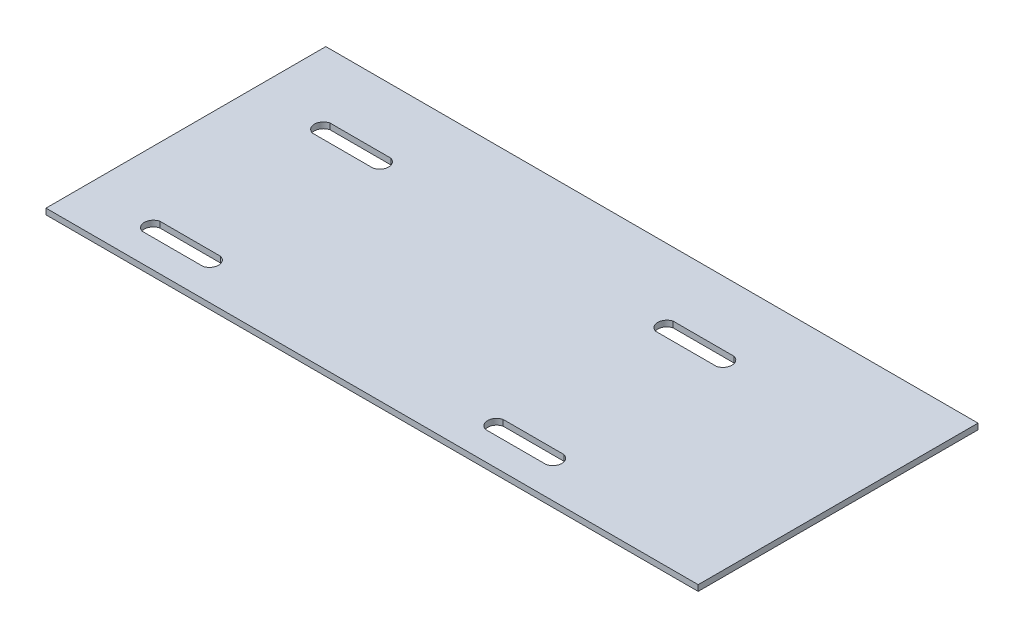
SolidWorks part; units mm, degrees
material "Plain Carbon Steel"
ref_plane "Front Plane" through (0, 0, 0) normal (0, 0, 1) x (1, 0, 0)
ref_plane "Top Plane" through (0, 0, 0) normal (0, 1, 0) x (1, 0, 0)
ref_plane "Right Plane" through (0, 0, 0) normal (1, 0, 0) x (0, 0, -1)
sketch "Sketch1" plane through (0, 0, 0) normal (0, 1, 0) x (1, 0, 0)
  line L0 (31.6679, -31.9514) -> (59.9621, -31.9514)
  line L1 (0, 85.0186) -> (303, 85.0186)
  line L2 (0, 85.0186) -> (0, -44.9814)
  line L3 (0, -44.9814) -> (303, -44.9814)
  line L4 (303, 85.0186) -> (303, -44.9814)
  line L5 (191.1627, 55.2372) -> (219.4569, 55.2372)
  line L7 (31.6679, 47.0872) -> (59.9621, 47.0872)
  line L8 (31.6679, -23.8014) -> (59.9621, -23.8014)
  line L9 (31.6679, 55.2372) -> (59.9621, 55.2372)
  line L10 (45.815, 55.2372) -> (45.815, 47.0872) construction
  line L13 (205.3098, 55.2372) -> (205.3098, 47.0872) construction
  line L14 (45.815, -23.8014) -> (45.815, -31.9514) construction
  line L15 (191.1627, 47.0872) -> (219.4569, 47.0872)
  line L18 (191.1627, -31.9514) -> (219.4569, -31.9514)
  line L19 (191.1627, -23.8014) -> (219.4569, -23.8014)
  line L20 (205.3098, -23.8014) -> (205.3098, -31.9514) construction
  arc A0 (31.6679, -23.8014) -> (31.6679, -31.9514) centre (32.7855, -27.8764) ccw
  arc A1 (59.9621, -23.8014) -> (59.9621, -31.9514) centre (58.8445, -27.8764) cw
  arc A2 (59.9621, 55.2372) -> (59.9621, 47.0872) centre (58.8445, 51.1622) cw
  arc A3 (31.6679, 55.2372) -> (31.6679, 47.0872) centre (32.7855, 51.1622) ccw
  arc A4 (191.1627, 55.2372) -> (191.1627, 47.0872) centre (192.2803, 51.1622) ccw
  arc A5 (219.4569, 55.2372) -> (219.4569, 47.0872) centre (218.3393, 51.1622) cw
  arc A6 (191.1627, -23.8014) -> (191.1627, -31.9514) centre (192.2803, -27.8764) ccw
  arc A7 (219.4569, -23.8014) -> (219.4569, -31.9514) centre (218.3393, -27.8764) cw
  dimension "D1" = 303
  dimension "D2" = 130
extrude "Boss-Extrude1" add sketch "Sketch1" along normal blind 2.73
